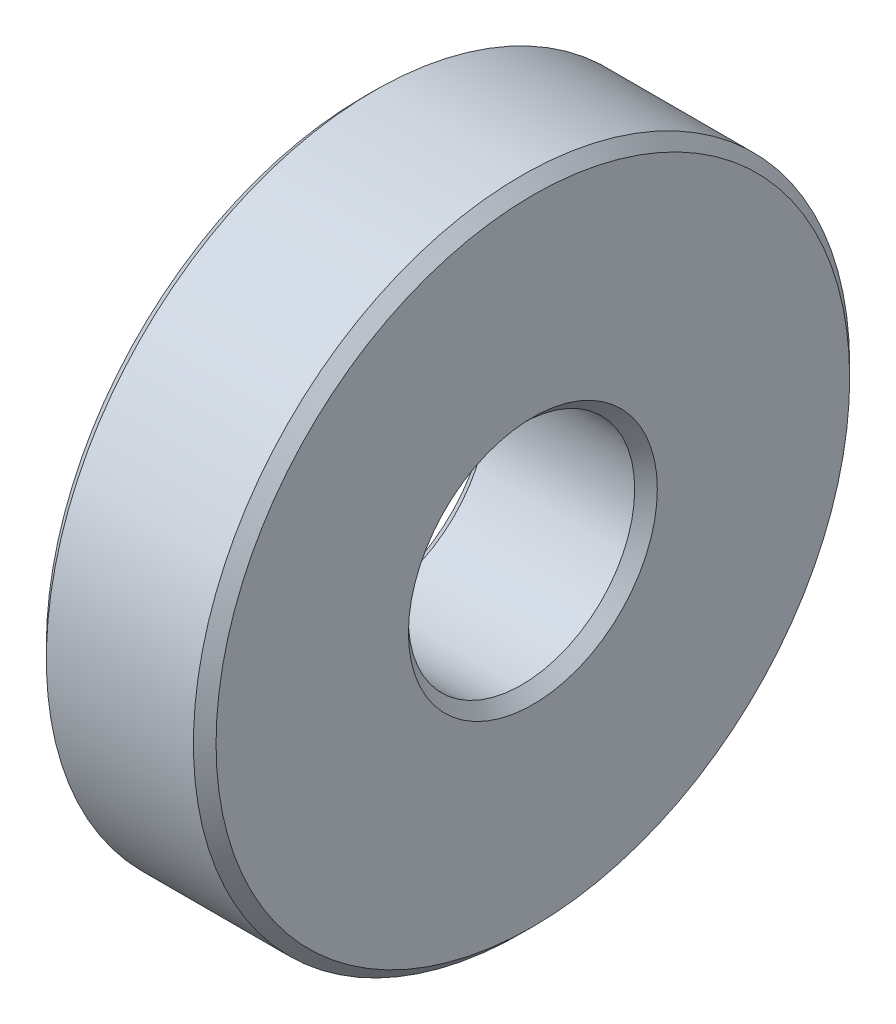
SolidWorks part; units mm, degrees
ref_plane "Alzado" through (0, 0, 0) normal (0, 0, 1) x (1, 0, 0)
ref_plane "Planta" through (0, 0, 0) normal (0, 1, 0) x (1, 0, 0)
ref_plane "Vista lateral" through (0, 0, 0) normal (1, 0, 0) x (0, 0, -1)
sketch "Croquis1" plane through (0, 0, 0) normal (1, 0, 0) x (0, 0, -1)
  circle A0 centre (0, 0) radius 2.9
  circle A1 centre (0, 0) radius 1
extrude "Saliente-Extruir1" add sketch "Croquis1" along normal blind 1.5
chamfer "Chaflán1" distance 0.1 angle 45 4 edges at (1.5, 0, -1) (1.5, 0, -2.9) (0, 0, -2.9) (0, 0, -1)
